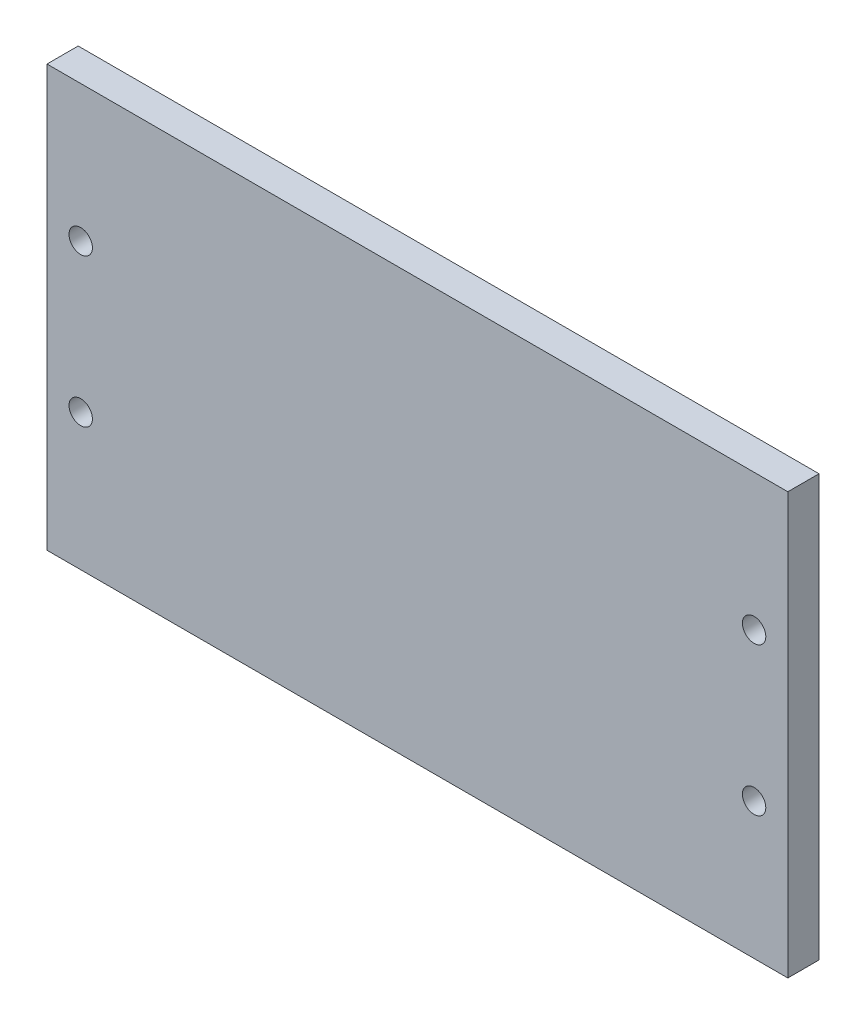
SolidWorks part; units mm, degrees
ref_plane "Front Plane" through (0, 0, 0) normal (0, 0, 1) x (1, 0, 0)
ref_plane "Top Plane" through (0, 0, 0) normal (0, 1, 0) x (1, 0, 0)
ref_plane "Right Plane" through (0, 0, 0) normal (1, 0, 0) x (0, 0, -1)
sketch "Sketch1" plane through (0, 0, 0) normal (0, 0, 1) x (1, 0, 0)
  line L1 (-95, 54) -> (95, 54)
  line L2 (-95, 54) -> (-95, -54)
  line L3 (-95, -54) -> (95, -54)
  line L4 (95, 54) -> (95, -54)
  line L5 (-95, 54) -> (95, -54) construction
  line L6 (-95, -54) -> (95, 54) construction
  point P0 (0, 0)
  dimension "D1" = 190
  dimension "D2" = 108
extrude "Boss-Extrude1" add sketch "Sketch1" along normal blind 8
sketch "Sketch2" plane through (0, 0, 8) normal (0, 0, 1) x (1, 0, 0)
  line L0 (0, 54) -> (0, 0) construction
  line L1 (95, 54) -> (-95, 54) construction
  line L2 (0, 0) -> (-86.35, 0) construction
  line L3 (-86.35, 19) -> (-86.35, -19) construction
  circle A0 centre (-86.35, 19) radius 3
  circle A1 centre (-86.35, -19) radius 3
  circle A2 centre (86.35, -19) radius 3
  circle A3 centre (86.35, 19) radius 3
  point P9 (-86.35, 0)
  dimension "D4" = 6
  dimension "D1" = 54
  dimension "D2" = 86.35
  dimension "D3" = 38
extrude "Cut-Extrude1" cut sketch "Sketch2" against normal through all contours A1 | A2 | A3 | A0
